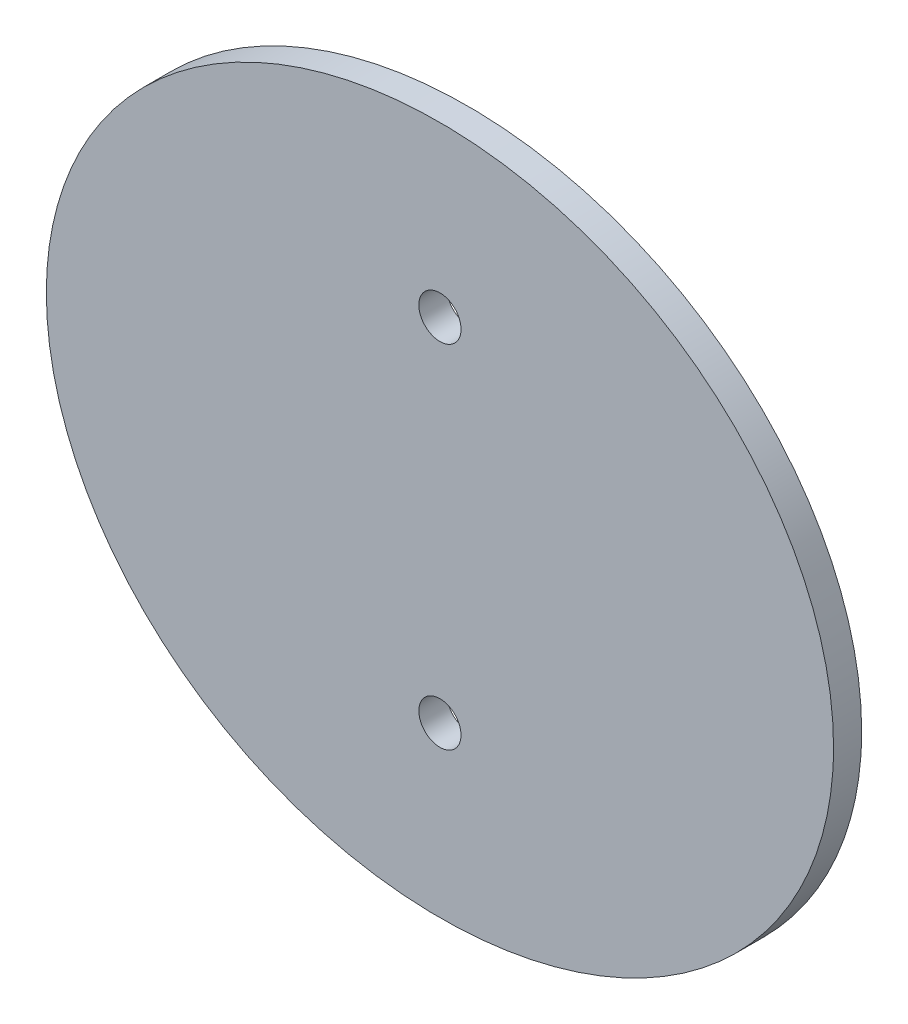
SolidWorks part; units mm, degrees
ref_plane "Front Plane" through (0, 0, 0) normal (0, 0, 1) x (1, 0, 0)
ref_plane "Top Plane" through (0, 0, 0) normal (0, 1, 0) x (1, 0, 0)
ref_plane "Right Plane" through (0, 0, 0) normal (1, 0, 0) x (0, 0, -1)
sketch "Sketch1" plane through (0, 0, 0) normal (0, 0, 1) x (1, 0, 0)
  line L0 (-20.4238, 0) -> (18.9684, 0) construction
  circle A0 centre (0, 12.5) radius 1.5
  circle A1 centre (0, -12.5) radius 1.5
  ellipse E0 centre (0, 0) end of major axis (28, 0) minor radius 24.5
  dimension "D3" = 3
  dimension "D1" = 49
  dimension "D2" = 56
  dimension "D4" = 25
extrude "Boss-Extrude1" add sketch "Sketch1" along normal blind 2
